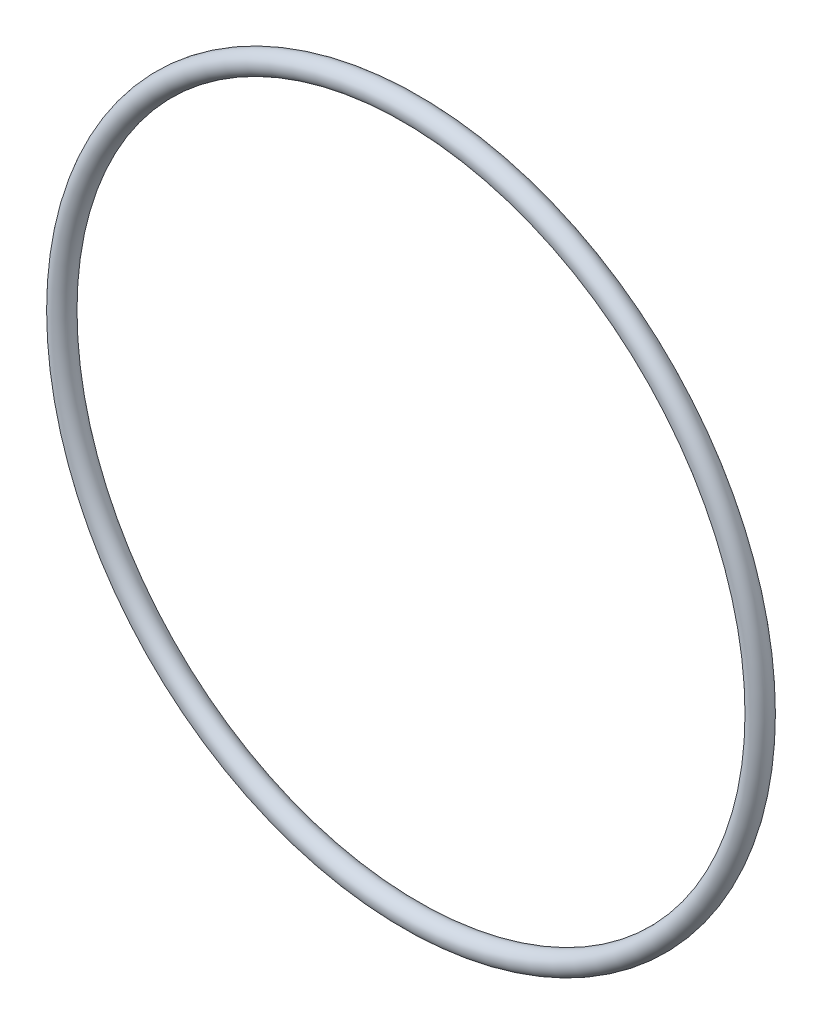
SolidWorks part; units mm, degrees
ref_plane "Front Plane" through (0, 0, 0) normal (0, 0, 1) x (1, 0, 0)
ref_plane "Top Plane" through (0, 0, 0) normal (0, 1, 0) x (1, 0, 0)
ref_plane "Right Plane" through (0, 0, 0) normal (1, 0, 0) x (0, 0, -1)
sketch "Sketch1" plane through (0, 0, 0) normal (1, 0, 0) x (0, 0, -1)
  line L0 (-21.7841, 0) -> (21.7841, 0) construction
  circle A0 centre (0, 48.7) radius 1.5
  point P4 (0, 0)
  dimension "D2" = 3
  dimension "D1" = 48.7
revolve "Revolve1" add sketch "Sketch1" angle 360 about L0
